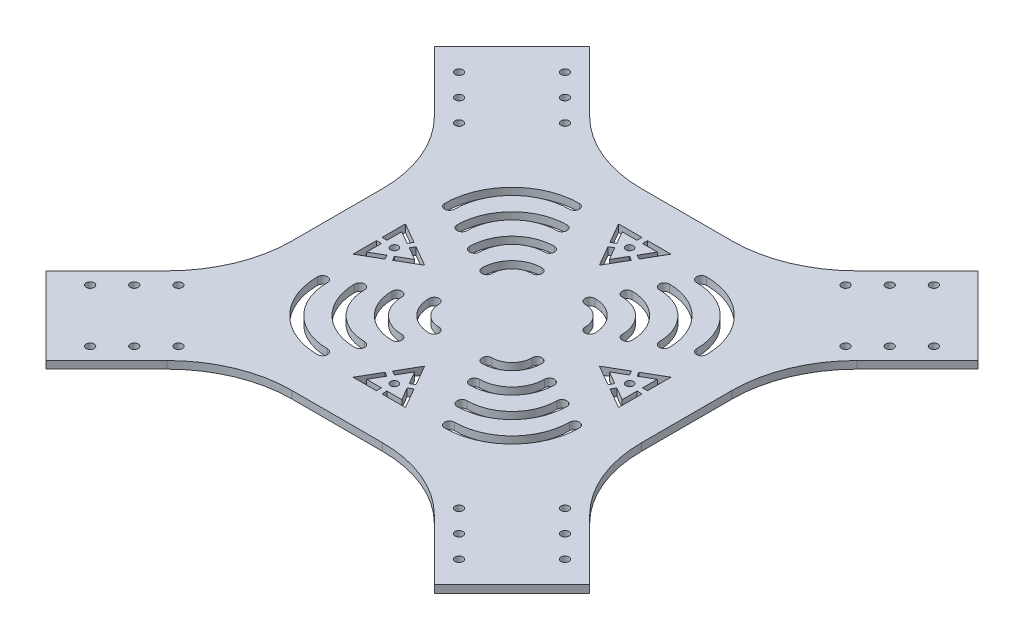
SolidWorks part; units mm, degrees
ref_plane "Ön Düzlem" through (0, 0, 0) normal (0, 0, 1) x (1, 0, 0)
ref_plane "Üst Düzlem" through (0, 0, 0) normal (0, 1, 0) x (1, 0, 0)
ref_plane "Sağ Düzlem" through (0, 0, 0) normal (1, 0, 0) x (0, 0, -1)
sketch "Çizim1" plane through (0, 0, 0) normal (0, 1, 0) x (1, 0, 0)
  line L0 (-108.8909, 77.7782) -> (-77.7782, 108.8909)
  line L1 (-70, -70) -> (70, -70)
  line L2 (-70, -70) -> (-70, 70)
  line L3 (-70, 70) -> (70, 70)
  line L4 (70, -70) -> (70, 70)
  line L5 (-70, -70) -> (70, 70) construction
  line L6 (-70, 70) -> (70, -70) construction
  line L7 (108.8909, 77.7782) -> (70, 38.8873)
  line L8 (-108.8909, 77.7782) -> (-70, 38.8873)
  line L9 (77.7782, 108.8909) -> (108.8909, 77.7782)
  line L10 (-77.7782, 108.8909) -> (-38.8873, 70)
  line L11 (77.7782, 108.8909) -> (38.8873, 70)
  line L12 (77.7782, -108.8909) -> (38.8873, -70)
  line L13 (108.8909, -77.7782) -> (77.7782, -108.8909)
  line L14 (108.8909, -77.7782) -> (70, -38.8873)
  line L15 (-108.8909, -77.7782) -> (-70, -38.8873)
  line L16 (-77.7782, -108.8909) -> (-108.8909, -77.7782)
  line L17 (-77.7782, -108.8909) -> (-38.8873, -70)
  point P0 (0, 0)
  dimension "D1" = 140
  dimension "D2" = 140
  dimension "D3" = 22
  dimension "D4" = 22
  dimension "D5" = 55
  dimension "D7" = 55
  dimension "D6" = 4
extrude "Yükseklik-Ekstrüzyon1" add sketch "Çizim1" along normal blind 3 contours L1 L4 L3 L2 | L10 L0 L8 L2 L3 | L16 L17 L1 L2 L15 | L13 L14 L4 L1 L12 | L9 L11 L3 L4 L7
fillet "Radyus1" radius 50 8 edges at (-38.8873, 1.5, -70) (38.8873, 1.5, -70) (70, 1.5, -38.8873) (70, 1.5, 38.8873) (38.8873, 1.5, 70) (-38.8873, 1.5, 70) (-70, 1.5, 38.8873) (-70, 1.5, -38.8873)
sketch "Çizim2" plane through (0, 3, 0) normal (0, 1, 0) x (1, 0, 0)
  line L0 (-1000, 0) -> (49000, 0) construction
  line L1 (0, -1000) -> (0, 49000) construction
  line L2 (-707.1068, -707.1068) -> (34648.2323, 34648.2323) construction
  line L3 (707.1068, -707.1068) -> (-34648.2323, 34648.2323) construction
  line L4 (-53.1865, -10.5) -> (-53.1865, 10.5)
  line L5 (-53.1865, 10.5) -> (-35, 0)
  line L6 (-35, 0) -> (-53.1865, -10.5)
  line L7 (-53.1865, -10.5) -> (-44.0933, 5.25) construction
  line L8 (-51.1865, 7.0359) -> (-46.0459, 4.0679)
  line L9 (-39, 0) -> (-51.1865, -7.0359)
  line L10 (-51.1865, -7.0359) -> (-51.1865, -1.1)
  line L11 (-46.0459, 4.0679) -> (-45.0459, 5.8)
  line L12 (-44.1406, 2.9679) -> (-43.1406, 4.7)
  line L13 (-44.1406, 2.9679) -> (-39, 0)
  line L14 (-51.1865, 7.0359) -> (-39, 0) construction
  line L15 (-44.1406, -2.9679) -> (-43.1406, -4.7)
  line L16 (-46.0459, -4.0679) -> (-45.0459, -5.8)
  line L17 (-51.1865, -1.1) -> (-53.1865, -1.1)
  line L18 (-51.1865, 1.1) -> (-53.1865, 1.1)
  line L19 (-51.1865, 1.1) -> (-51.1865, 7.0359)
  line L20 (-51.1865, -7.0359) -> (-51.1865, 7.0359) construction
  line L21 (0, 35) -> (-10.5, 53.1865)
  line L22 (-10.5, 53.1865) -> (10.5, 53.1865)
  line L23 (10.5, 53.1865) -> (0, 35)
  line L24 (1.1, 51.1865) -> (7.0359, 51.1865)
  line L25 (1.1, 51.1865) -> (1.1, 53.1865)
  line L26 (-1.1, 51.1865) -> (-1.1, 53.1865)
  line L27 (-7.0359, 51.1865) -> (-1.1, 51.1865)
  line L28 (0, 39) -> (-7.0359, 51.1865)
  line L29 (-4.0679, 46.0459) -> (-5.8, 45.0459)
  line L30 (-2.9679, 44.1406) -> (-4.7, 43.1406)
  line L31 (2.9679, 44.1406) -> (0, 39)
  line L32 (2.9679, 44.1406) -> (4.7, 43.1406)
  line L33 (4.0679, 46.0459) -> (5.8, 45.0459)
  line L34 (7.0359, 51.1865) -> (4.0679, 46.0459)
  line L35 (35, 0) -> (53.1865, 10.5)
  line L36 (53.1865, 10.5) -> (53.1865, -10.5)
  line L37 (53.1865, -10.5) -> (35, 0)
  line L38 (51.1865, -1.1) -> (51.1865, -7.0359)
  line L39 (51.1865, -1.1) -> (53.1865, -1.1)
  line L40 (51.1865, 1.1) -> (53.1865, 1.1)
  line L41 (51.1865, 7.0359) -> (51.1865, 1.1)
  line L42 (39, 0) -> (51.1865, 7.0359)
  line L43 (46.0459, 4.0679) -> (45.0459, 5.8)
  line L44 (44.1406, 2.9679) -> (43.1406, 4.7)
  line L45 (44.1406, -2.9679) -> (39, 0)
  line L46 (44.1406, -2.9679) -> (43.1406, -4.7)
  line L47 (46.0459, -4.0679) -> (45.0459, -5.8)
  line L48 (51.1865, -7.0359) -> (46.0459, -4.0679)
  line L49 (0, -35) -> (10.5, -53.1865)
  line L50 (10.5, -53.1865) -> (-10.5, -53.1865)
  line L51 (-10.5, -53.1865) -> (0, -35)
  line L52 (-1.1, -51.1865) -> (-7.0359, -51.1865)
  line L53 (-1.1, -51.1865) -> (-1.1, -53.1865)
  line L54 (1.1, -51.1865) -> (1.1, -53.1865)
  line L55 (7.0359, -51.1865) -> (1.1, -51.1865)
  line L56 (0, -39) -> (7.0359, -51.1865)
  line L57 (4.0679, -46.0459) -> (5.8, -45.0459)
  line L58 (2.9679, -44.1406) -> (4.7, -43.1406)
  line L59 (-2.9679, -44.1406) -> (0, -39)
  line L60 (-2.9679, -44.1406) -> (-4.7, -43.1406)
  line L61 (-4.0679, -46.0459) -> (-5.8, -45.0459)
  line L62 (-7.0359, -51.1865) -> (-4.0679, -46.0459)
  arc A0 (52.4558, 25.4558) -> (25.4558, 52.4558) centre (25.4558, 25.4558) ccw
  arc A5 (-25.4558, 50.4558) -> (-50.4558, 25.4558) centre (-25.4558, 25.4558) ccw construction
  arc A6 (-25.4558, 52.4558) -> (-52.4558, 25.4558) centre (-25.4558, 25.4558) ccw
  arc A7 (-25.4558, 48.4558) -> (-48.4558, 25.4558) centre (-25.4558, 25.4558) ccw
  arc A8 (-25.4558, 48.4558) -> (-25.4558, 52.4558) centre (-25.4558, 50.4558) ccw
  arc A9 (-52.4558, 25.4558) -> (-48.4558, 25.4558) centre (-50.4558, 25.4558) ccw
  arc A10 (-20.5061, 40.5061) -> (-40.5061, 20.5061) centre (-20.5061, 20.5061) ccw construction
  arc A11 (-20.5061, 42.5061) -> (-42.5061, 20.5061) centre (-20.5061, 20.5061) ccw
  arc A12 (-20.5061, 38.5061) -> (-38.5061, 20.5061) centre (-20.5061, 20.5061) ccw
  arc A13 (-20.5061, 38.5061) -> (-20.5061, 42.5061) centre (-20.5061, 40.5061) ccw
  arc A14 (-42.5061, 20.5061) -> (-38.5061, 20.5061) centre (-40.5061, 20.5061) ccw
  arc A15 (-15.5563, 30.5563) -> (-30.5563, 15.5563) centre (-15.5563, 15.5563) ccw construction
  arc A16 (-15.5563, 32.5563) -> (-32.5563, 15.5563) centre (-15.5563, 15.5563) ccw
  arc A17 (-15.5563, 28.5563) -> (-28.5563, 15.5563) centre (-15.5563, 15.5563) ccw
  arc A18 (-15.5563, 28.5563) -> (-15.5563, 32.5563) centre (-15.5563, 30.5563) ccw
  arc A19 (-32.5563, 15.5563) -> (-28.5563, 15.5563) centre (-30.5563, 15.5563) ccw
  arc A20 (-10.6066, 20.6066) -> (-20.6066, 10.6066) centre (-10.6066, 10.6066) ccw construction
  arc A21 (-10.6066, 22.6066) -> (-22.6066, 10.6066) centre (-10.6066, 10.6066) ccw
  arc A22 (-10.6066, 18.6066) -> (-18.6066, 10.6066) centre (-10.6066, 10.6066) ccw
  arc A23 (-10.6066, 18.6066) -> (-10.6066, 22.6066) centre (-10.6066, 20.6066) ccw
  arc A24 (-22.6066, 10.6066) -> (-18.6066, 10.6066) centre (-20.6066, 10.6066) ccw
  arc A25 (25.4558, 52.4558) -> (25.4558, 48.4558) centre (25.4558, 50.4558) ccw
  arc A26 (48.4558, 25.4558) -> (25.4558, 48.4558) centre (25.4558, 25.4558) ccw
  arc A27 (48.4558, 25.4558) -> (52.4558, 25.4558) centre (50.4558, 25.4558) ccw
  arc A28 (42.5061, 20.5061) -> (20.5061, 42.5061) centre (20.5061, 20.5061) ccw
  arc A29 (20.5061, 42.5061) -> (20.5061, 38.5061) centre (20.5061, 40.5061) ccw
  arc A30 (38.5061, 20.5061) -> (20.5061, 38.5061) centre (20.5061, 20.5061) ccw
  arc A31 (38.5061, 20.5061) -> (42.5061, 20.5061) centre (40.5061, 20.5061) ccw
  arc A32 (32.5563, 15.5563) -> (15.5563, 32.5563) centre (15.5563, 15.5563) ccw
  arc A33 (15.5563, 32.5563) -> (15.5563, 28.5563) centre (15.5563, 30.5563) ccw
  arc A34 (28.5563, 15.5563) -> (15.5563, 28.5563) centre (15.5563, 15.5563) ccw
  arc A35 (28.5563, 15.5563) -> (32.5563, 15.5563) centre (30.5563, 15.5563) ccw
  arc A36 (22.6066, 10.6066) -> (10.6066, 22.6066) centre (10.6066, 10.6066) ccw
  arc A37 (10.6066, 22.6066) -> (10.6066, 18.6066) centre (10.6066, 20.6066) ccw
  arc A38 (18.6066, 10.6066) -> (10.6066, 18.6066) centre (10.6066, 10.6066) ccw
  arc A39 (18.6066, 10.6066) -> (22.6066, 10.6066) centre (20.6066, 10.6066) ccw
  arc A40 (50.4558, 25.4558) -> (25.4558, 50.4558) centre (25.4558, 25.4558) ccw construction
  arc A41 (40.5061, 20.5061) -> (20.5061, 40.5061) centre (20.5061, 20.5061) ccw construction
  arc A42 (30.5563, 15.5563) -> (15.5563, 30.5563) centre (15.5563, 15.5563) ccw construction
  arc A43 (20.6066, 10.6066) -> (10.6066, 20.6066) centre (10.6066, 10.6066) ccw construction
  arc A44 (25.4558, -52.4558) -> (52.4558, -25.4558) centre (25.4558, -25.4558) ccw
  arc A45 (52.4558, -25.4558) -> (48.4558, -25.4558) centre (50.4558, -25.4558) ccw
  arc A46 (25.4558, -48.4558) -> (48.4558, -25.4558) centre (25.4558, -25.4558) ccw
  arc A47 (25.4558, -48.4558) -> (25.4558, -52.4558) centre (25.4558, -50.4558) ccw
  arc A48 (20.5061, -42.5061) -> (42.5061, -20.5061) centre (20.5061, -20.5061) ccw
  arc A49 (42.5061, -20.5061) -> (38.5061, -20.5061) centre (40.5061, -20.5061) ccw
  arc A50 (20.5061, -38.5061) -> (38.5061, -20.5061) centre (20.5061, -20.5061) ccw
  arc A51 (20.5061, -38.5061) -> (20.5061, -42.5061) centre (20.5061, -40.5061) ccw
  arc A52 (15.5563, -32.5563) -> (32.5563, -15.5563) centre (15.5563, -15.5563) ccw
  arc A53 (32.5563, -15.5563) -> (28.5563, -15.5563) centre (30.5563, -15.5563) ccw
  arc A54 (15.5563, -28.5563) -> (28.5563, -15.5563) centre (15.5563, -15.5563) ccw
  arc A55 (15.5563, -28.5563) -> (15.5563, -32.5563) centre (15.5563, -30.5563) ccw
  arc A56 (10.6066, -22.6066) -> (22.6066, -10.6066) centre (10.6066, -10.6066) ccw
  arc A57 (22.6066, -10.6066) -> (18.6066, -10.6066) centre (20.6066, -10.6066) ccw
  arc A58 (10.6066, -18.6066) -> (18.6066, -10.6066) centre (10.6066, -10.6066) ccw
  arc A59 (10.6066, -18.6066) -> (10.6066, -22.6066) centre (10.6066, -20.6066) ccw
  arc A60 (25.4558, -50.4558) -> (50.4558, -25.4558) centre (25.4558, -25.4558) ccw construction
  arc A61 (20.5061, -40.5061) -> (40.5061, -20.5061) centre (20.5061, -20.5061) ccw construction
  arc A62 (15.5563, -30.5563) -> (30.5563, -15.5563) centre (15.5563, -15.5563) ccw construction
  arc A63 (10.6066, -20.6066) -> (20.6066, -10.6066) centre (10.6066, -10.6066) ccw construction
  arc A64 (-52.4558, -25.4558) -> (-25.4558, -52.4558) centre (-25.4558, -25.4558) ccw
  arc A65 (-25.4558, -52.4558) -> (-25.4558, -48.4558) centre (-25.4558, -50.4558) ccw
  arc A66 (-48.4558, -25.4558) -> (-25.4558, -48.4558) centre (-25.4558, -25.4558) ccw
  arc A67 (-48.4558, -25.4558) -> (-52.4558, -25.4558) centre (-50.4558, -25.4558) ccw
  arc A68 (-42.5061, -20.5061) -> (-20.5061, -42.5061) centre (-20.5061, -20.5061) ccw
  arc A69 (-20.5061, -42.5061) -> (-20.5061, -38.5061) centre (-20.5061, -40.5061) ccw
  arc A70 (-38.5061, -20.5061) -> (-20.5061, -38.5061) centre (-20.5061, -20.5061) ccw
  arc A71 (-38.5061, -20.5061) -> (-42.5061, -20.5061) centre (-40.5061, -20.5061) ccw
  arc A72 (-32.5563, -15.5563) -> (-15.5563, -32.5563) centre (-15.5563, -15.5563) ccw
  arc A73 (-15.5563, -32.5563) -> (-15.5563, -28.5563) centre (-15.5563, -30.5563) ccw
  arc A74 (-28.5563, -15.5563) -> (-15.5563, -28.5563) centre (-15.5563, -15.5563) ccw
  arc A75 (-28.5563, -15.5563) -> (-32.5563, -15.5563) centre (-30.5563, -15.5563) ccw
  arc A76 (-22.6066, -10.6066) -> (-10.6066, -22.6066) centre (-10.6066, -10.6066) ccw
  arc A77 (-10.6066, -22.6066) -> (-10.6066, -18.6066) centre (-10.6066, -20.6066) ccw
  arc A78 (-18.6066, -10.6066) -> (-10.6066, -18.6066) centre (-10.6066, -10.6066) ccw
  arc A79 (-18.6066, -10.6066) -> (-22.6066, -10.6066) centre (-20.6066, -10.6066) ccw
  arc A80 (-50.4558, -25.4558) -> (-25.4558, -50.4558) centre (-25.4558, -25.4558) ccw construction
  arc A81 (-40.5061, -20.5061) -> (-20.5061, -40.5061) centre (-20.5061, -20.5061) ccw construction
  arc A82 (-30.5563, -15.5563) -> (-15.5563, -30.5563) centre (-15.5563, -15.5563) ccw construction
  arc A83 (-20.6066, -10.6066) -> (-10.6066, -20.6066) centre (-10.6066, -10.6066) ccw construction
  circle A84 centre (-47.1244, 0) radius 1.5
  circle A85 centre (0, 47.1244) radius 1.5
  circle A86 centre (47.1244, 0) radius 1.5
  circle A87 centre (0, -47.1244) radius 1.5
  point P15 (43.1335, 43.1335)
  point P21 (-43.1335, 43.1335)
  point P29 (-34.6482, 34.6482)
  point P37 (-26.163, 26.163)
  point P45 (-17.6777, 17.6777)
  point P55 (34.6482, 34.6482)
  point P63 (26.163, 26.163)
  point P71 (17.6777, 17.6777)
  point P79 (43.1335, -43.1335)
  point P87 (34.6482, -34.6482)
  point P95 (26.163, -26.163)
  point P103 (17.6777, -17.6777)
  point P111 (-43.1335, -43.1335)
  point P119 (-34.6482, -34.6482)
  point P127 (-26.163, -26.163)
  point P135 (-17.6777, -17.6777)
  point P140 (-53.1865, 0)
  dimension "D3" = 4
  dimension "D4" = 60
  dimension "D6" = 25
  dimension "D7" = 20
  dimension "D8" = 15
  dimension "D9" = 10
  dimension "D17" = 3
  dimension "D1" = 45
  dimension "D2" = 45
  dimension "D5" = 60
  dimension "D10" = 25
  dimension "D11" = 12
  dimension "D12" = 12
  dimension "D13" = 12
  dimension "D14" = 19.9497
  dimension "D15" = 35
  dimension "D16" = 21
  dimension "D19" = 1.1
  dimension "D20" = 1.1
  dimension "D21" = 4
  dimension "D18" = 2
extrude "Kes-Ekstrüzyon1" cut sketch "Çizim2" against normal blind 4 contours A6 A9 A7 A8 | A11 A14 A12 A13 | A21 A24 A22 A23 | A38 A39 A36 A37 | A34 A35 A32 A33 | A30 A31 A28 A29 | A26 A27 A0 A25 | A66 A67 A64 A65 | A70 A71 A68 A69 | A74 A75 A72 A73 | A78 A79 A76 A77 | L60 L59 L56 L58 L49 L51 | L52 L62 L61 L51 L50 L53 | L57 L56 L55 L54 L50 L49 | A50 A51 A48 A49 | A58 A59 A56 A57 | A54 A55 A52 A53 | A46 A47 A44 A45 | L43 L42 L41 L40 L36 L35 | L38 L48 L47 L37 L36 L39 | L46 L45 L42 L44 L35 L37 | A86 | L32 L31 L28 L30 L21 L23 | L24 L34 L33 L23 L22 L25 | A85 | L29 L28 L27 L26 L22 L21 | L9 L15 L6 L5 L12 L13 | L10 L17 L4 L6 L16 L9 | L18 L19 L8 L11 L5 L4 | A84 | A16 A19 A17 A18 | A87
sketch "Çizim3" plane through (0, 3, 0) normal (0, 1, 0) x (1, 0, 0)
  line L0 (-93.3345, 93.3345) -> (0, 0) construction
  line L1 (-108.8909, 77.7782) -> (-77.7782, 108.8909) construction
  line L2 (-93.3345, 93.3345) -> (-103.9411, 82.7279) construction
  line L3 (-108.8909, 77.7782) -> (-84.6447, 53.532) construction
  line L4 (-103.9411, 82.7279) -> (-70.2735, 49.0603) construction
  line L5 (-77.7782, 108.8909) -> (-53.532, 84.6447) construction
  circle A0 centre (-95.1023, 73.8891) radius 1.6
  circle A1 centre (-86.2635, 65.0503) radius 1.6
  circle A2 centre (-77.4246, 56.2114) radius 1.6
  circle A3 centre (-56.2114, 77.4246) radius 1.6
  circle A4 centre (-65.0503, 86.2635) radius 1.6
  circle A5 centre (-73.8891, 95.1023) radius 1.6
  circle A24 centre (56.2114, 77.4246) radius 1.6
  circle A43 centre (65.0503, 86.2635) radius 1.6
  circle A44 centre (73.8891, 95.1023) radius 1.6
  circle A45 centre (77.4246, 56.2114) radius 1.6
  circle A46 centre (86.2635, 65.0503) radius 1.6
  circle A47 centre (95.1023, 73.8891) radius 1.6
  circle A48 centre (77.4246, -56.2114) radius 1.6
  circle A49 centre (86.2635, -65.0503) radius 1.6
  circle A50 centre (95.1023, -73.8891) radius 1.6
  circle A51 centre (56.2114, -77.4246) radius 1.6
  circle A52 centre (65.0503, -86.2635) radius 1.6
  circle A53 centre (73.8891, -95.1023) radius 1.6
  circle A54 centre (-56.2114, -77.4246) radius 1.6
  circle A55 centre (-65.0503, -86.2635) radius 1.6
  circle A56 centre (-73.8891, -95.1023) radius 1.6
  circle A57 centre (-77.4246, -56.2114) radius 1.6
  circle A58 centre (-86.2635, -65.0503) radius 1.6
  circle A59 centre (-95.1023, -73.8891) radius 1.6
  dimension "D2" = 3.2
  dimension "D1" = 7
  dimension "D3" = 12.5
  dimension "D4" = 12.5
  dimension "D5" = 12.5
  dimension "D6" = 7
  dimension "D7" = 15
  dimension "D9" = 15
  dimension "D8" = 4
extrude "Kes-Ekstrüzyon2" cut sketch "Çizim3" against normal blind 50
